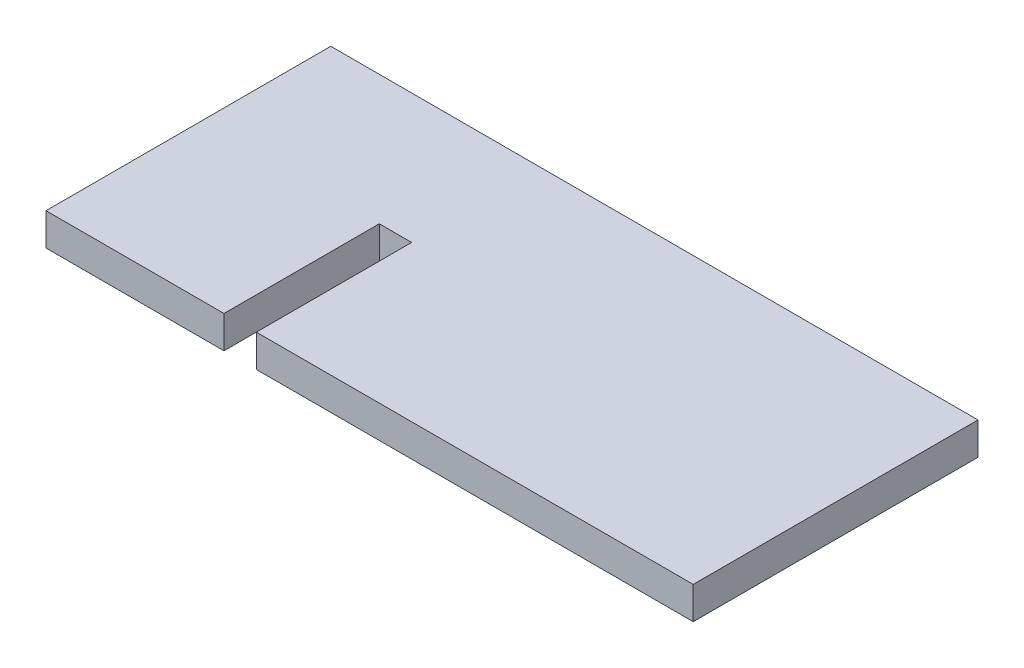
SolidWorks part; units mm, degrees
ref_plane "Front Plane" through (0, 0, 0) normal (0, 0, 1) x (1, 0, 0)
ref_plane "Top Plane" through (0, 0, 0) normal (0, 1, 0) x (1, 0, 0)
ref_plane "Right Plane" through (0, 0, 0) normal (1, 0, 0) x (0, 0, -1)
sketch "Sketch2" plane through (0, 0, 0) normal (0, 1, 0) x (1, 0, 0)
  line L1 (0, 0) -> (63.5, 0)
  line L2 (0, 0) -> (0, 27.94)
  line L3 (0, 27.94) -> (63.5, 27.94)
  line L4 (63.5, 0) -> (63.5, 27.94)
  dimension "D1" = 63.5
  dimension "D2" = 27.94
extrude "Boss-Extrude1" add sketch "Sketch2" along normal blind 3.175
sketch "Sketch3" plane through (0, 0, 0) normal (0, -1, 0) x (1, 0, 0)
  line L0 (0, 0) -> (63.5, 0) construction
  line L1 (17.4625, 0) -> (20.6375, 0)
  line L2 (17.4625, 0) -> (17.4625, -15.24)
  line L3 (17.4625, -15.24) -> (20.6375, -15.24)
  line L4 (20.6375, 0) -> (20.6375, -15.24)
  line L5 (0, -27.94) -> (0, 0) construction
  dimension "D1" = 15.24
  dimension "D2" = 17.4625
  dimension "D3" = 3.175
extrude "Cut-Extrude1" cut sketch "Sketch3" against normal through all
equation "\"support_thickness\"=0.125"
equation "\"support_height\"= 1.1"
equation "\"support_width\"=1.5"
equation "\"D1@Sketch2\"=\"support_width\"+1"
equation "\"D2@Sketch2\"=\"support_height\""
equation "\"D1@Boss-Extrude1\"=\"support_thickness\""
equation "\"D1@Sketch3\"=\"support_height\"-0.5"
equation "\"D2@Sketch3\"=(\"support_width\"-\"support_thickness\")/2"
equation "\"D3@Sketch3\"=\"support_thickness\""
